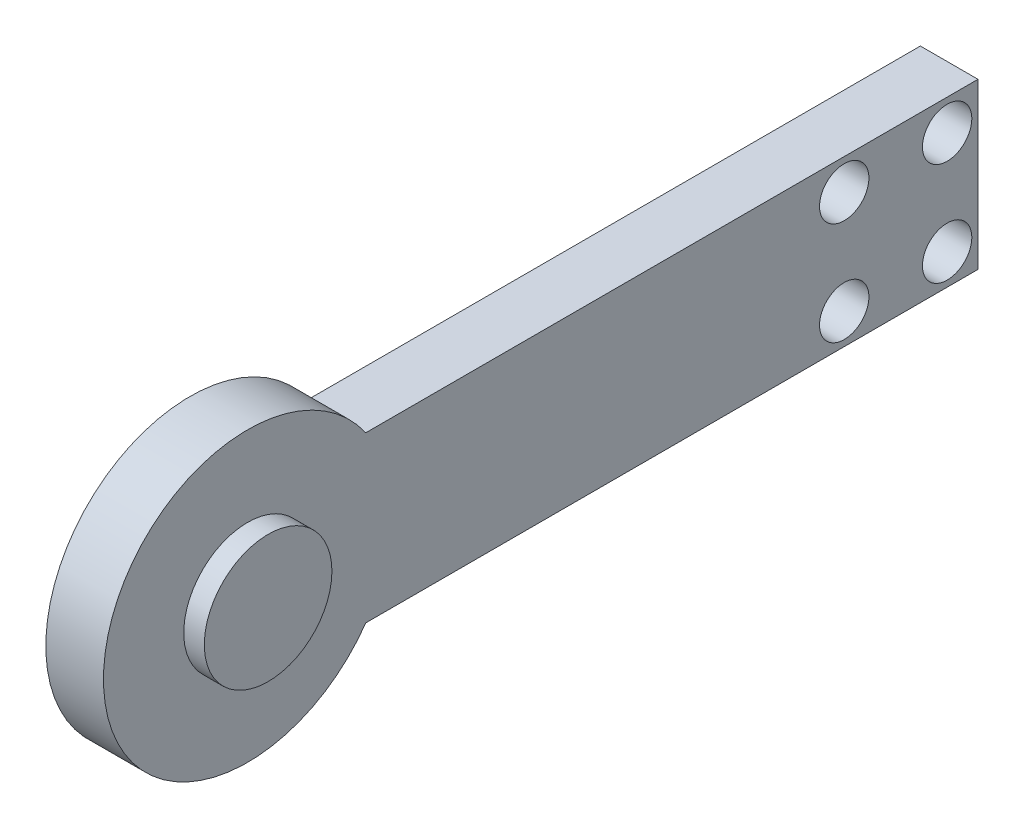
SolidWorks part; units mm, degrees
ref_plane "前视基准面" through (0, 0, 0) normal (0, 0, 1) x (1, 0, 0)
ref_plane "上视基准面" through (0, 0, 0) normal (0, 1, 0) x (1, 0, 0)
ref_plane "右视基准面" through (0, 0, 0) normal (1, 0, 0) x (0, 0, -1)
sketch "草图1" plane through (0, 0, 0) normal (1, 0, 0) x (0, 0, -1)
  line L1 (177.4456, -20) -> (28.7228, -20)
  line L2 (177.4456, -20) -> (177.4456, 20)
  line L3 (177.4456, 20) -> (28.7228, 20)
  line L5 (103.0842, 20) -> (103.0842, -20) construction
  line L6 (177.4456, 0) -> (103.0842, 0) construction
  arc A0 (28.7228, 20) -> (28.7228, -20) centre (0, 0) ccw
  point P3 (103.0842, 0)
  dimension "D1" = 70
  dimension "D2" = 40
extrude "凸台-拉伸1" add sketch "草图1" along normal blind 14
sketch "草图4" plane through (14, 0, 0) normal (1, 0, 0) x (0, 0, -1)
  circle A0 centre (0, 0) radius 15.5
  dimension "D1" = 31
extrude "凸台-拉伸2" add sketch "草图4" along normal blind 5
sketch "草图5" plane through (14, 0, 0) normal (1, 0, 0) x (0, 0, -1)
  line L0 (177.4456, 0) -> (0, 0) construction
  line L1 (177.4456, -20) -> (177.4456, 20) construction
  circle A0 centre (169.9456, 12.5) radius 6
  circle A1 centre (144.9456, 12.5) radius 6
  circle A2 centre (144.9456, -12.5) radius 6
  circle A3 centre (169.9456, -12.5) radius 6
  dimension "D2" = 12
  dimension "D1" = 7.5
  dimension "D4" = 25
  dimension "D3" = 2
extrude "切除-拉伸1" cut sketch "草图5" against normal through all both and the other way through all
